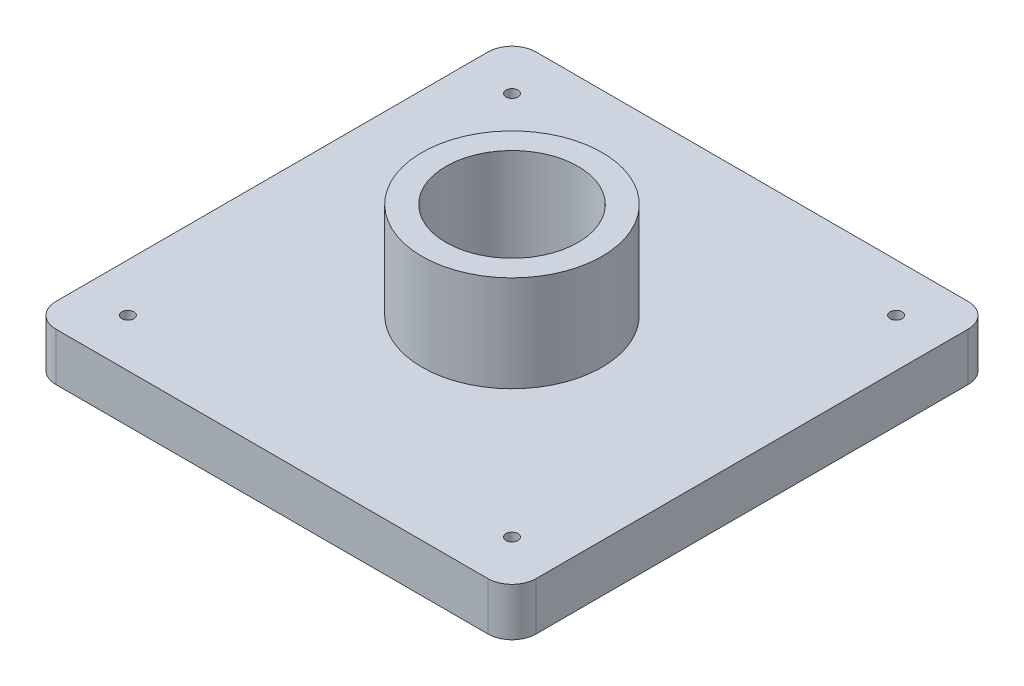
SolidWorks part; units mm, degrees
material "Plain Carbon Steel"
ref_plane "Front Plane" through (0, 0, 0) normal (0, 0, 1) x (1, 0, 0)
ref_plane "Top Plane" through (0, 0, 0) normal (0, 1, 0) x (1, 0, 0)
ref_plane "Right Plane" through (0, 0, 0) normal (1, 0, 0) x (0, 0, -1)
sketch "Sketch1" plane through (0, 0, 0) normal (0, 1, 0) x (1, 0, 0)
  line L1 (-90, -100) -> (90, -100)
  line L2 (-100, -90) -> (-100, 90)
  line L3 (-90, 100) -> (90, 100)
  line L4 (100, -90) -> (100, 90)
  arc A1 (-90, -100) -> (-100, -90) centre (-90, -90) cw
  arc A2 (90, -100) -> (100, -90) centre (90, -90) ccw
  arc A3 (90, 100) -> (100, 90) centre (90, 90) cw
  arc A4 (-100, 90) -> (-90, 100) centre (-90, 90) cw
  dimension "D1" = 10
  dimension "D2" = 100
  dimension "D3" = 200
  dimension "D4" = 200
  dimension "D5" = 100
extrude "Boss-Extrude1" add sketch "Sketch1" along normal blind 20
sketch "Sketch2" plane through (0, 20, 0) normal (0, 1, 0) x (1, 0, 0)
  circle A0 centre (0, 0) radius 37.5
  dimension "D1" = 75
extrude "Boss-Extrude2" add sketch "Sketch2" along normal blind 40 contours A0
sketch "Sketch3" plane through (0, 20, 0) normal (0, 1, 0) x (1, 0, 0)
  line L0 (-100, 90) -> (-100, -90) construction
  line L1 (90, 100) -> (-90, 100) construction
  line L2 (-90, -100) -> (90, -100) construction
  line L3 (100, -90) -> (100, 90) construction
  circle A0 centre (-80, 80) radius 2.5
  circle A1 centre (80, 80) radius 2.5
  circle A2 centre (80, -80) radius 2.5
  circle A3 centre (-80, -80) radius 2.5
  dimension "D1" = 5
  dimension "D2" = 20
  dimension "D3" = 20
  dimension "D4" = 20
  dimension "D5" = 20
extrude "Cut-Extrude1" cut sketch "Sketch3" against normal up to next
sketch "Sketch4" plane through (0, 60, 0) normal (0, 1, 0) x (1, 0, 0)
  line L0 (0, 27.5) -> (0, 37.5)
  circle A0 centre (0, 0) radius 27.5
  circle A1 centre (0, 0) radius 37.5 construction
  dimension "D1" = 10
extrude "Cut-Extrude2" cut sketch "Sketch4" against normal through all contours A0
